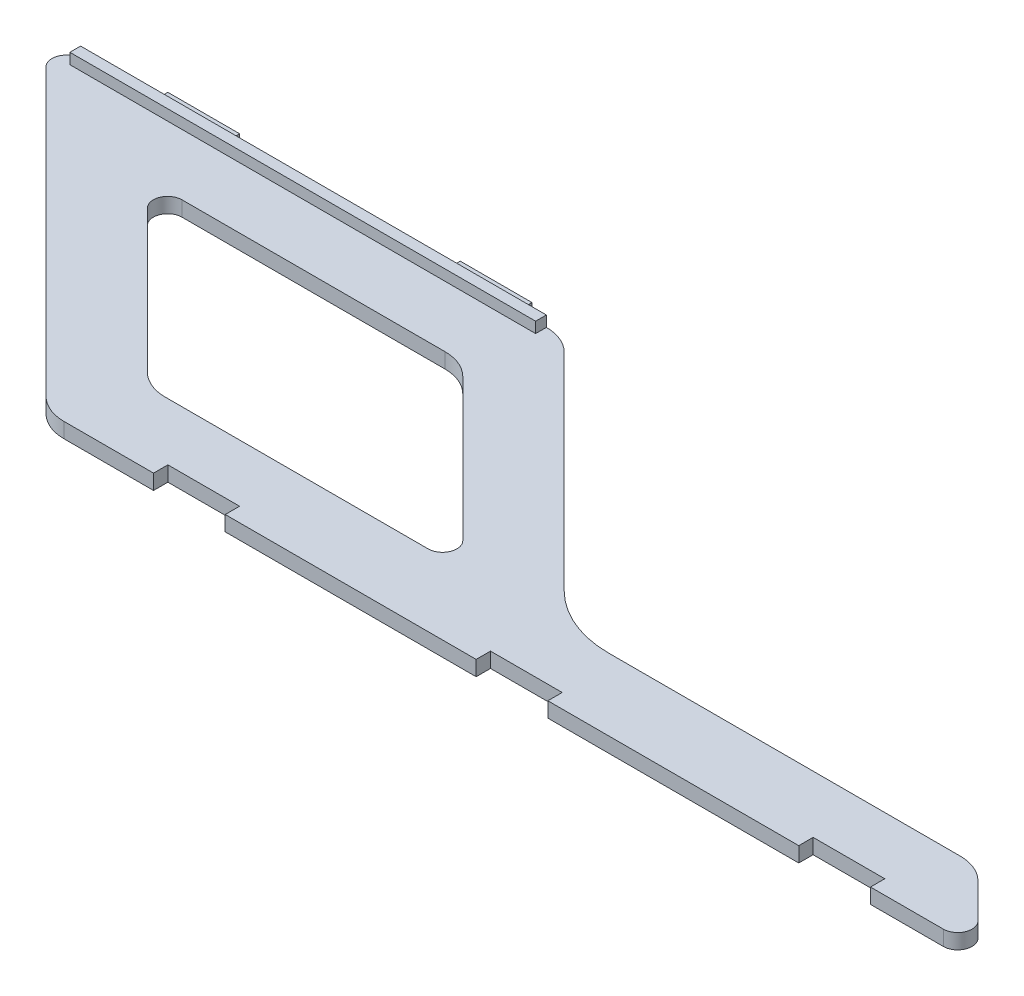
SolidWorks part; units mm, degrees
ref_plane "Front Plane" through (0, 0, 0) normal (0, 0, 1) x (1, 0, 0)
ref_plane "Top Plane" through (0, 0, 0) normal (0, 1, 0) x (1, 0, 0)
ref_plane "Right Plane" through (0, 0, 0) normal (1, 0, 0) x (0, 0, -1)
sketch "Sketch1" plane through (0, 0, 0) normal (0, 1, 0) x (1, 0, 0)
  line L0 (4.8284, 0) -> (15, 0)
  line L1 (15, 0) -> (15, 2)
  line L2 (15, 2) -> (25, 2)
  line L3 (25, 2) -> (25, 0)
  line L4 (25, 0) -> (55.78, 0)
  line L5 (55.78, 0) -> (55.78, 2)
  line L6 (55.78, 2) -> (65.78, 2)
  line L7 (65.78, 2) -> (65.78, 0)
  line L8 (65.78, 0) -> (69.7947, 0)
  line L9 (74.0374, -1.7574) -> (102.8866, -30.6066)
  line L10 (3.4142, -3.4142) -> (43.2426, -43.2426)
  line L11 (47.4853, -45) -> (60, -45)
  line L12 (113.4932, -35) -> (162.5147, -35)
  line L14 (28.9706, -10) -> (65.6526, -10)
  line L15 (69.8952, -11.7574) -> (89.7237, -31.5858)
  line L16 (88.3094, -35) -> (51.6274, -35)
  line L17 (47.3848, -33.2426) -> (27.5563, -13.4142)
  line L18 (171.5858, -41.5858) -> (166.7574, -36.7574)
  line L19 (70, -45) -> (105, -45)
  line L24 (60, -45) -> (60, -43)
  line L25 (60, -43) -> (70, -43)
  line L26 (70, -45) -> (70, -43)
  line L28 (105, -45) -> (105, -43)
  line L29 (105, -43) -> (115, -43)
  line L30 (115, -45) -> (115, -43)
  line L32 (150, -45) -> (150, -43)
  line L33 (150, -43) -> (160, -43)
  line L34 (160, -45) -> (160, -43)
  line L35 (115, -45) -> (150, -45)
  line L36 (160, -45) -> (170.1716, -45)
  arc A0 (43.2426, -43.2426) -> (47.4853, -45) centre (47.4853, -39) ccw
  arc A1 (113.4932, -35) -> (102.8866, -30.6066) centre (113.4932, -20) cw
  arc A2 (74.0374, -1.7574) -> (69.7947, 0) centre (69.7947, -6) ccw
  arc A3 (3.4142, -3.4142) -> (4.8284, 0) centre (4.8284, -2) cw
  arc A4 (166.7574, -36.7574) -> (162.5147, -35) centre (162.5147, -41) ccw
  arc A5 (170.1716, -45) -> (171.5858, -41.5858) centre (170.1716, -43) ccw
  arc A6 (27.5563, -13.4142) -> (28.9706, -10) centre (28.9706, -12) cw
  arc A7 (69.8952, -11.7574) -> (65.6526, -10) centre (65.6526, -16) ccw
  arc A8 (88.3094, -35) -> (89.7237, -31.5858) centre (88.3094, -33) ccw
  arc A9 (51.6274, -35) -> (47.3848, -33.2426) centre (51.6274, -29) cw
  point P25 (72.28, 0)
  point P28 (0, 0)
  point P33 (175, -45)
  point P54 (150, -44)
  dimension "D20" = 6
  dimension "D21" = 15
  dimension "D22" = 6
  dimension "D23" = 2
  dimension "D24" = 6
  dimension "D25" = 2
  dimension "D26" = 2
  dimension "D27" = 6
  dimension "D28" = 2
  dimension "D29" = 6
  dimension "D1" = 2
  dimension "D2" = 10
  dimension "D3" = 10
  dimension "D4" = 2
  dimension "D5" = 2
  dimension "D6" = 2
  dimension "D7" = 30.78
  dimension "D8" = 15
  dimension "D9" = 135
  dimension "D10" = 135
  dimension "D11" = 45
  dimension "D12" = 10
  dimension "D13" = 10
  dimension "D14" = 175
  dimension "D15" = 6.5
  dimension "D16" = 10
  dimension "D17" = 10
  dimension "D18" = 10
  dimension "D19" = 45
  dimension "D30" = 10
  dimension "D31" = 2
  dimension "D32" = 35
  dimension "D33" = 10
  dimension "D34" = 2
  dimension "D35" = 35
  dimension "D36" = 10
  dimension "D37" = 2
  dimension "D38" = 35
extrude "Boss-Extrude1" add sketch "Sketch1" along normal blind 2.1
sketch "Sketch2" plane through (0, 2.1, 0) normal (0, 1, 0) x (1, 0, 0)
  line L1 (4.8284, 0) -> (69.7947, 0)
  line L2 (4.8284, 0) -> (4.8284, -1.5)
  line L3 (4.8284, -1.5) -> (69.7947, -1.5)
  line L4 (69.7947, 0) -> (69.7947, -1.5)
  point P5 (69.7947, 0)
  dimension "D1" = 1.5
extrude "Boss-Extrude2" add sketch "Sketch2" along normal blind 1.5
